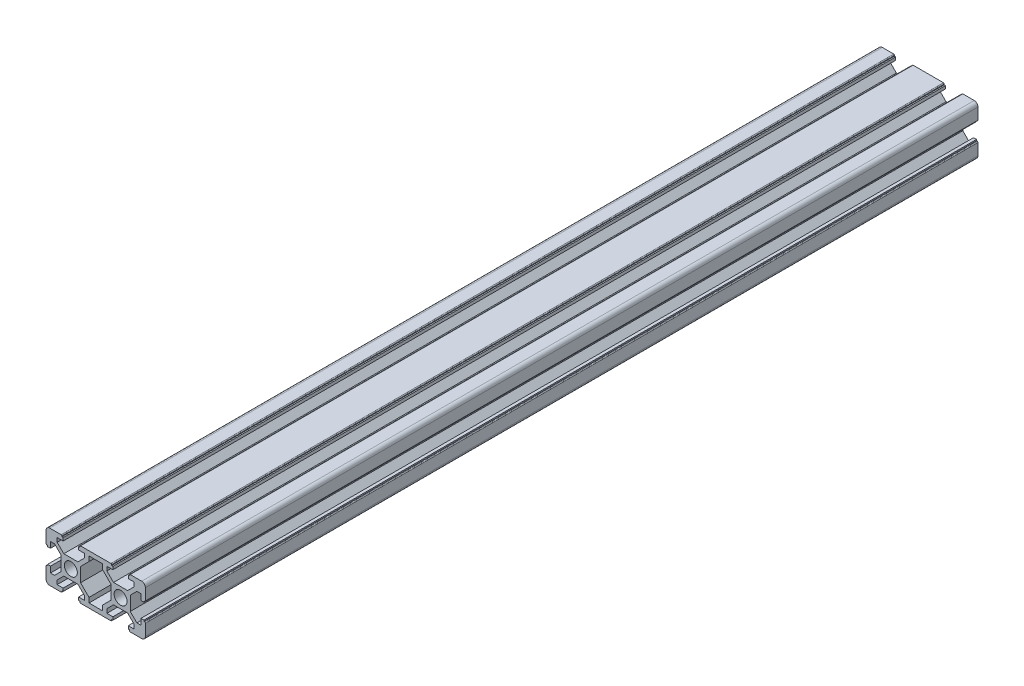
SolidWorks part; units mm, degrees
ref_plane "前视基准面" through (0, 0, 0) normal (0, 0, 1) x (1, 0, 0)
ref_plane "上视基准面" through (0, 0, 0) normal (0, 1, 0) x (1, 0, 0)
ref_plane "右视基准面" through (0, 0, 0) normal (1, 0, 0) x (0, 0, -1)
sketch "草图1" plane through (0, 0, 0) normal (0, 0, 1) x (1, 0, 0)
  line L0 (0, 0) -> (0, -41497.3383) construction
  line L1 (0, 0) -> (41497.3383, 0) construction
  line L2 (-13.9, 0) -> (-13.9, 2.8393)
  line L3 (-13.9, 2.8393) -> (-16.5607, 5.5)
  line L4 (-16.5607, 5.5) -> (-18.2, 5.5)
  line L5 (-18.2, 5.5) -> (-18.2, 3.1)
  line L6 (-18.2, 3.1) -> (-19.4, 3.1)
  line L7 (-19.4, 3.1) -> (-19.4, 3.6)
  line L8 (-19.4, 3.6) -> (-20, 3.6)
  line L9 (-20, 3.6) -> (-20, 10)
  line L10 (-20, 10) -> (-13.6, 10)
  line L11 (-13.6, 10) -> (-13.6, 9.4)
  line L12 (-13.6, 9.4) -> (-13.1, 9.4)
  line L13 (-13.1, 9.4) -> (-13.1, 8.2)
  line L14 (-13.1, 8.2) -> (-15.5, 8.2)
  line L15 (-15.5, 6.5607) -> (-12.8393, 3.9)
  line L16 (-12.8393, 3.9) -> (-7.1607, 3.9)
  line L17 (-4.5, 6.5607) -> (-7.1607, 3.9)
  line L18 (-4.5, 6.5607) -> (-4.5, 8.2)
  line L19 (-4.5, 8.2) -> (-6.9, 8.2)
  line L20 (-6.9, 8.2) -> (-6.9, 9.4)
  line L21 (-6.9, 9.4) -> (-6.4, 9.4)
  line L22 (-6.4, 9.4) -> (-6.4, 10)
  line L23 (-6.4, 10) -> (6.4, 10)
  line L24 (-15.5, 8.2) -> (-15.5, 6.5607)
  line L25 (-10, 0) -> (-20, 10) construction
  line L26 (-6.1, -2.8393) -> (-6.1, 2.8393)
  line L27 (-6.1, 2.8393) -> (-2.7, 6.2393)
  line L28 (-2.7, 6.2393) -> (-2.7, 8.2)
  line L29 (-2.7, 8.2) -> (2.7, 8.2)
  line L30 (-10, 0) -> (0, 10) construction
  line L31 (13.9, 0) -> (13.9, 2.8393)
  line L32 (6.1, -2.8393) -> (6.1, 2.8393)
  line L33 (4.5, 6.5607) -> (7.1607, 3.9)
  line L34 (12.8393, 3.9) -> (7.1607, 3.9)
  line L35 (6.1, 2.8393) -> (2.7, 6.2393)
  line L36 (2.7, 6.2393) -> (2.7, 8.2)
  line L37 (4.5, 6.5607) -> (4.5, 8.2)
  line L38 (6.4, 9.4) -> (6.4, 10)
  line L39 (6.9, 9.4) -> (6.4, 9.4)
  line L40 (6.9, 8.2) -> (6.9, 9.4)
  line L41 (4.5, 8.2) -> (6.9, 8.2)
  line L42 (13.1, 9.4) -> (13.1, 8.2)
  line L43 (13.6, 9.4) -> (13.1, 9.4)
  line L44 (13.6, 10) -> (13.6, 9.4)
  line L45 (20, 10) -> (13.6, 10)
  line L46 (20, 3.6) -> (20, 10)
  line L47 (19.4, 3.6) -> (20, 3.6)
  line L48 (19.4, 3.1) -> (19.4, 3.6)
  line L49 (18.2, 3.1) -> (19.4, 3.1)
  line L50 (18.2, 5.5) -> (18.2, 3.1)
  line L51 (16.5607, 5.5) -> (18.2, 5.5)
  line L52 (13.9, 2.8393) -> (16.5607, 5.5)
  line L53 (15.5, 6.5607) -> (12.8393, 3.9)
  line L54 (15.5, 8.2) -> (15.5, 6.5607)
  line L55 (13.1, 8.2) -> (15.5, 8.2)
  line L56 (15.5, -6.5607) -> (12.8393, -3.9)
  line L57 (13.9, -2.8393) -> (16.5607, -5.5)
  line L58 (16.5607, -5.5) -> (18.2, -5.5)
  line L59 (18.2, -5.5) -> (18.2, -3.1)
  line L60 (18.2, -3.1) -> (19.4, -3.1)
  line L61 (19.4, -3.1) -> (19.4, -3.6)
  line L62 (19.4, -3.6) -> (20, -3.6)
  line L63 (12.8393, -3.9) -> (7.1607, -3.9)
  line L64 (13.9, 0) -> (13.9, -2.8393)
  line L65 (13.1, -8.2) -> (15.5, -8.2)
  line L66 (15.5, -8.2) -> (15.5, -6.5607)
  line L67 (20, -3.6) -> (20, -10)
  line L68 (20, -10) -> (13.6, -10)
  line L69 (13.6, -10) -> (13.6, -9.4)
  line L70 (13.6, -9.4) -> (13.1, -9.4)
  line L71 (13.1, -9.4) -> (13.1, -8.2)
  line L72 (4.5, -8.2) -> (6.9, -8.2)
  line L73 (6.9, -8.2) -> (6.9, -9.4)
  line L74 (6.9, -9.4) -> (6.4, -9.4)
  line L75 (6.4, -9.4) -> (6.4, -10)
  line L76 (4.5, -6.5607) -> (4.5, -8.2)
  line L77 (2.7, -6.2393) -> (2.7, -8.2)
  line L78 (6.1, -2.8393) -> (2.7, -6.2393)
  line L79 (4.5, -6.5607) -> (7.1607, -3.9)
  line L80 (-2.7, -8.2) -> (2.7, -8.2)
  line L81 (-2.7, -6.2393) -> (-2.7, -8.2)
  line L82 (-6.1, -2.8393) -> (-2.7, -6.2393)
  line L83 (-4.5, -6.5607) -> (-7.1607, -3.9)
  line L84 (-4.5, -8.2) -> (-6.9, -8.2)
  line L85 (-4.5, -6.5607) -> (-4.5, -8.2)
  line L86 (-6.4, -10) -> (6.4, -10)
  line L87 (-6.4, -9.4) -> (-6.4, -10)
  line L88 (-6.9, -9.4) -> (-6.4, -9.4)
  line L89 (-6.9, -8.2) -> (-6.9, -9.4)
  line L90 (-13.1, -9.4) -> (-13.1, -8.2)
  line L91 (-13.6, -9.4) -> (-13.1, -9.4)
  line L92 (-13.6, -10) -> (-13.6, -9.4)
  line L93 (-15.5, -8.2) -> (-15.5, -6.5607)
  line L94 (-13.1, -8.2) -> (-15.5, -8.2)
  line L95 (-12.8393, -3.9) -> (-7.1607, -3.9)
  line L96 (-15.5, -6.5607) -> (-12.8393, -3.9)
  line L97 (-13.9, 0) -> (-13.9, -2.8393)
  line L98 (-13.9, -2.8393) -> (-16.5607, -5.5)
  line L99 (-19.4, -3.6) -> (-20, -3.6)
  line L100 (-19.4, -3.1) -> (-19.4, -3.6)
  line L101 (-18.2, -3.1) -> (-19.4, -3.1)
  line L102 (-18.2, -5.5) -> (-18.2, -3.1)
  line L103 (-16.5607, -5.5) -> (-18.2, -5.5)
  line L104 (-20, -3.6) -> (-20, -10)
  line L105 (-20, -10) -> (-13.6, -10)
  circle A0 centre (-10, 0) radius 2.6
  circle A1 centre (10, 0) radius 2.6
  point P50 (0, 8.2)
  point P95 (6.1, 0)
  point P96 (-6.1, 0)
  dimension "D1" = 5.2
  dimension "D2" = 45
  dimension "D3" = 1.5
  dimension "D4" = 20
  dimension "D5" = 40
  dimension "D6" = 0.75
  dimension "D7" = 7.2
  dimension "D8" = 6.2
  dimension "D9" = 6.1
  dimension "D10" = 1.8
  dimension "D11" = 1.2
  dimension "D12" = 12.2
  dimension "D13" = 5.4
  dimension "D14" = 11
  dimension "D15" = 1.5
  dimension "D16" = 0.75
extrude "凸台-拉伸1" add sketch "草图1" along normal mid plane 335
fillet "圆角1" radius 1.5 4 edges at (20, -10, 0) (20, 10, 0) (-20, -10, 0) (-20, 10, 0)
fillet "圆角2" radius 0.3 12 edges at (-6.4, 10, 0) (-13.6, 10, 0) (-20, 3.6, 0) (-20, -3.6, 0) (-13.6, -10, 0) (-6.4, -10, 0) (6.4, -10, 0) (20, -3.6, 0) (20, 3.6, 0) (13.6, -10, 0) (13.6, 10, 0) (6.4, 10, 0)
equation "\"D6@草图1\"=1/2*\"D3@草图1\""
equation "\"D16@草图1\"=0.5*\"D15@草图1\""
